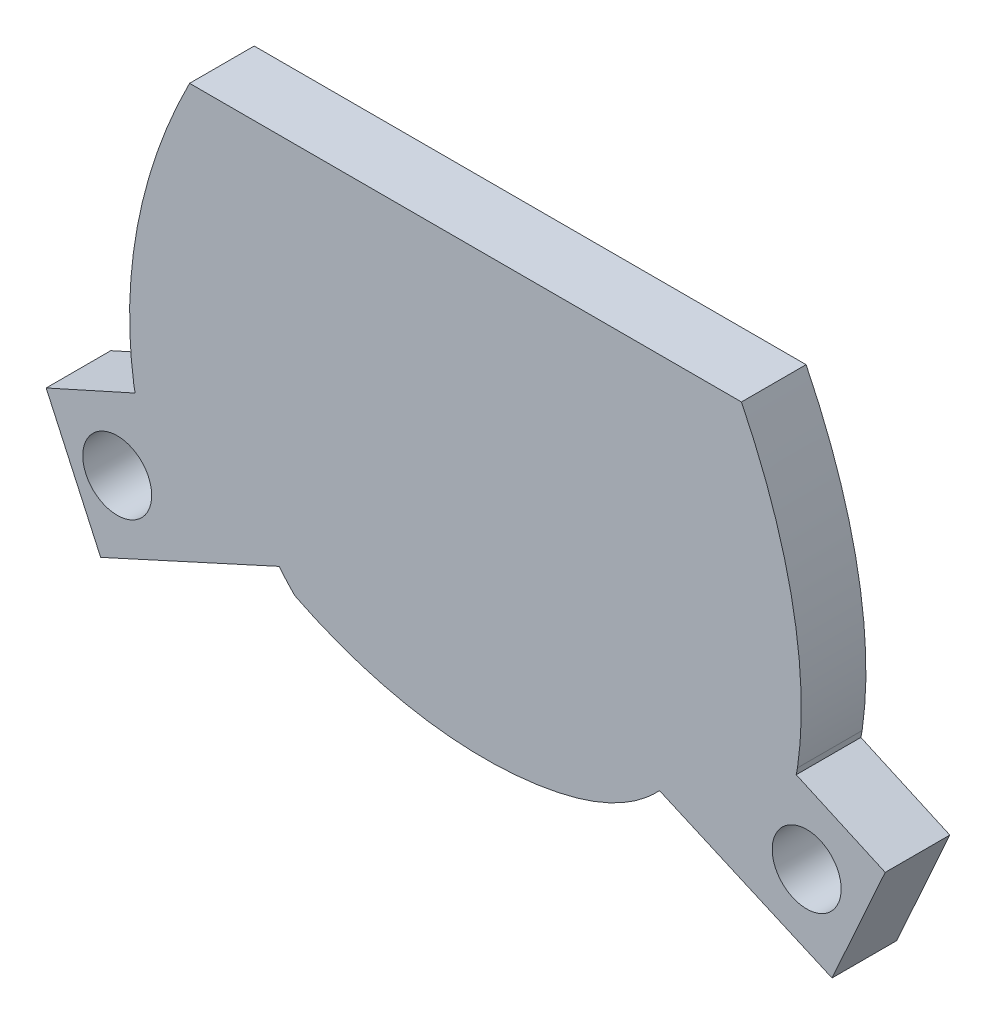
SolidWorks part; units mm, degrees
ref_plane "Front Plane" through (0, 0, 0) normal (0, 0, 1) x (1, 0, 0)
ref_plane "Top Plane" through (0, 0, 0) normal (0, 1, 0) x (1, 0, 0)
ref_plane "Right Plane" through (0, 0, 0) normal (1, 0, 0) x (0, 0, -1)
sketch "Sketch1" plane through (0, 0, 0) normal (0, 0, 1) x (1, 0, 0)
  line L0 (-9.7409, -2.7228) -> (-8.4762, -5.4954)
  line L1 (-8.4762, -5.4954) -> (-4.3346, -3.6062)
  line L2 (6.3963, 5.0645) -> (-6.4128, 5.0645)
  line L3 (8.4984, -5.4628) -> (4.4942, -3.6991)
  line L5 (8.4984, -5.4628) -> (9.7323, -2.7228)
  line L6 (9.7323, -2.7228) -> (7.6676, -1.793)
  line L8 (-9.7409, -2.7228) -> (-7.6762, -1.793)
  circle A0 centre (-8.0918, -3.658) radius 0.8
  circle A1 centre (7.9099, -3.5699) radius 0.8
  spline S1 degree 3 poles (-7.706, -1.64) (-7.9241, -0.1854) (-7.6754, 2.1493) (-6.7969, 4.3106) (-6.4128, 5.0645) knots 0 0 0 0 0.611703 0.967799 0.967799 0.967799 0.967799
  spline S2 degree 3 poles (6.3963, 5.0645) (6.678, 4.489) (7.2634, 3.0919) (7.7911, 0.8785) (7.8136, -0.7988) (7.7033, -1.5944) (7.6966, -1.64) knots 0.013512 0.013512 0.013512 0.013512 0.127684 0.281512 0.41537 0.423528 0.423528 0.423528 0.423528
  spline S3 degree 3 poles (-4.3346, -3.6062) (-4.2201, -3.7469) (-4.0989, -3.8823) (-3.972, -4.0121) knots 0 0 0 0 0.126751 0.126751 0.126751 0.126751
  spline S4 degree 1 poles (7.6966, -1.64) (7.6676, -1.793) knots 0 0 1 1
  spline S5 degree 1 poles (-7.706, -1.64) (-7.6762, -1.793) knots 0 0 1 1
  spline S6 degree 3 poles (5.0056, -2.4713) (4.93, -2.7032) (4.7147, -3.6564) (3.4472, -4.841) (2.0326, -5.1625) (1.8395, -5.833) knots 0.459785 0.459785 0.459785 0.459785 0.542607 0.788691 1 1 1 1 construction
  spline S7 degree 3 poles (4.4942, -3.6991) (3.7514, -4.4895) (0.8182, -5.497) (-2.2531, -4.8734) (-3.972, -4.0121) knots 0 0 0 0 0.353901 1 1 1 1
  spline S8 degree 3 poles (-5.0654, -2.4713) (-4.542, -3.5182) (-3.7686, -4.3562) (-2.7451, -4.9855) knots 0.470308 0.470308 0.470308 0.470308 0.870624 0.870624 0.870624 0.870624 construction
extrude "Boss-Extrude1" add sketch "Sketch1" against normal blind 1.5 from offset 2
